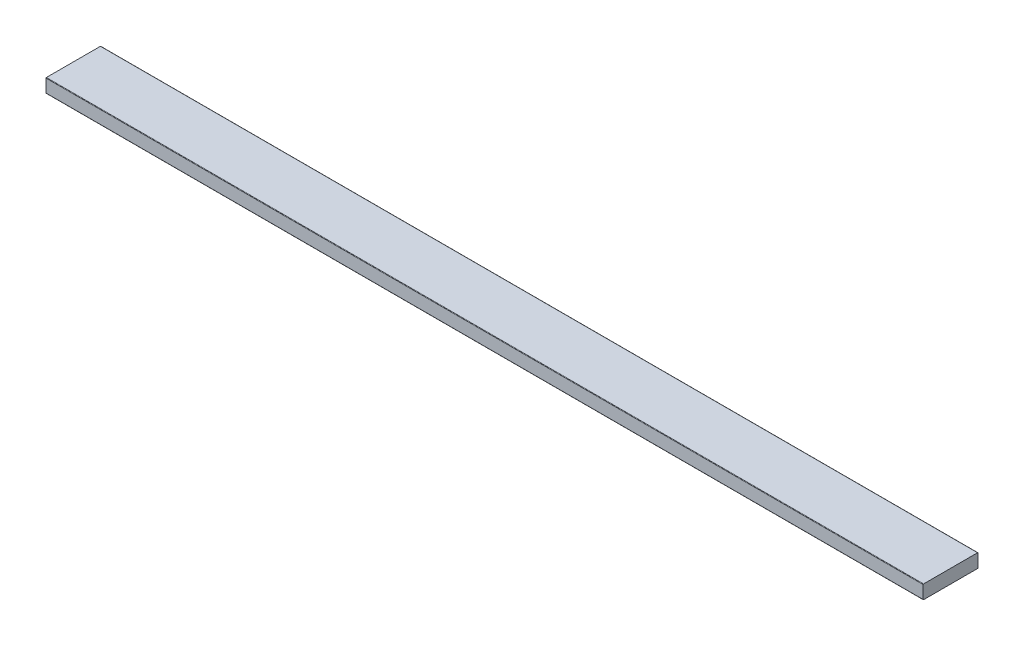
SolidWorks part; units mm, degrees
ref_plane "Front Plane" through (0, 0, 0) normal (0, 0, 1) x (1, 0, 0)
ref_plane "Top Plane" through (0, 0, 0) normal (0, 1, 0) x (1, 0, 0)
ref_plane "Right Plane" through (0, 0, 0) normal (1, 0, 0) x (0, 0, -1)
sketch "Sketch1" plane through (0, 0, 0) normal (0, 1, 0) x (1, 0, 0)
  line L1 (304.8, -19.05) -> (-304.8, -19.05)
  line L2 (304.8, -19.05) -> (304.8, 19.05)
  line L3 (304.8, 19.05) -> (-304.8, 19.05)
  line L4 (-304.8, -19.05) -> (-304.8, 19.05)
  line L5 (304.8, -19.05) -> (-304.8, 19.05) construction
  line L6 (304.8, 19.05) -> (-304.8, -19.05) construction
  point P0 (0, 0)
  dimension "Length" = 609.6
  dimension "Width" = 38.1
sketch "Sketch2" plane through (0, 0, 0) normal (1, 0, 0) x (0, 0, -1)
  line L0 (19.05, 4.7625) -> (19.05, -4.7625) construction
  point P2 (19.05, 0)
  dimension "Thickness" = 9.525
sketch "Sketch3" plane through (0, 0, 0) normal (0, 1, 0) x (1, 0, 0)
  line L1 (-304.8, 19.05) -> (304.8, 19.05)
  line L2 (-304.8, 19.05) -> (-304.8, -19.05)
  line L3 (-304.8, -19.05) -> (304.8, -19.05)
  line L4 (304.8, 19.05) -> (304.8, -19.05)
extrude "Boss-Extrude1" add sketch "Sketch3" against normal up to vertex (4.7625 mm away) and the other way up to vertex (4.7625 mm away) up to point (0, -4.7625, -19.05) other way up to point (0, 4.7625, -19.05)
fillet "Fillet1" radius 0.3143 4 edges at (0, -4.7625, 19.05) (0, -4.7625, -19.05) (0, 4.7625, -19.05) (0, 4.7625, 19.05)
equation "\"D1@Fillet1\" = \"Thickness@Sketch2\" * .033"
